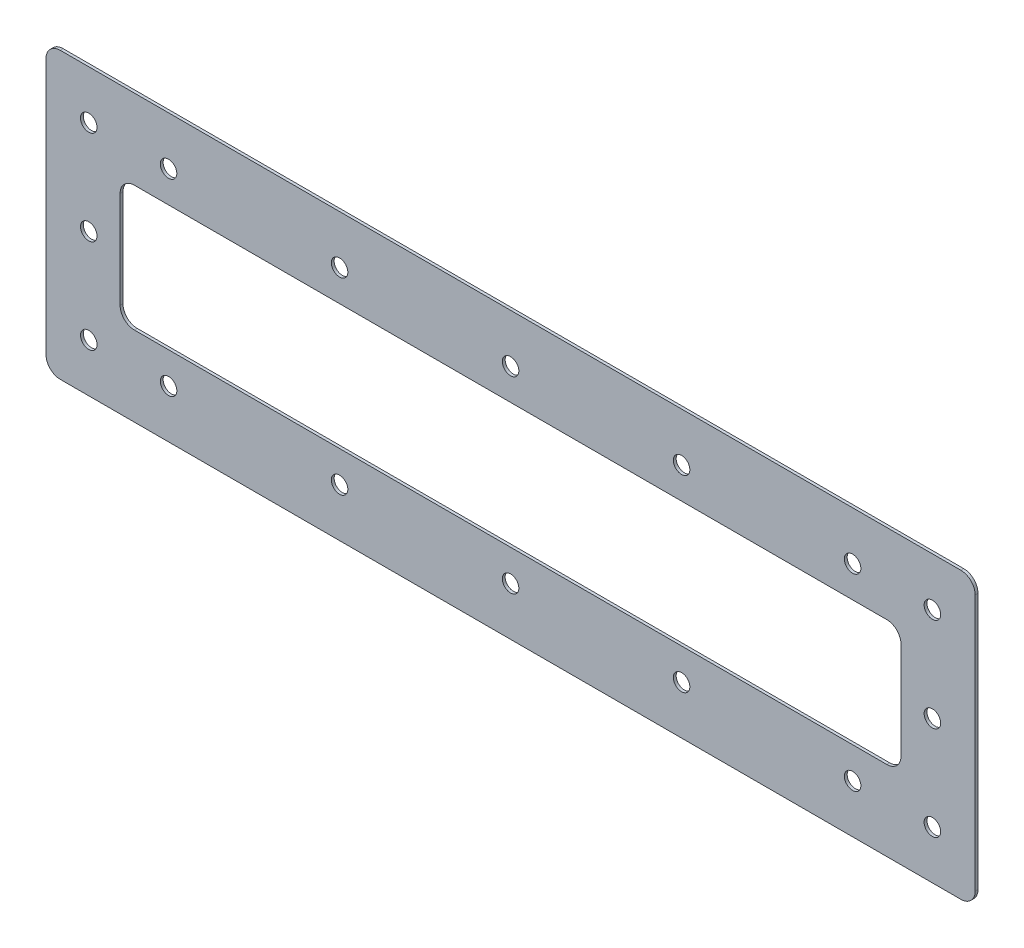
SolidWorks part; units mm, degrees
ref_plane "Front Plane" through (0, 0, 0) normal (0, 0, 1) x (1, 0, 0)
ref_plane "Top Plane" through (0, 0, 0) normal (0, 1, 0) x (1, 0, 0)
ref_plane "Right Plane" through (0, 0, 0) normal (1, 0, 0) x (0, 0, -1)
sketch "Sketch1" plane through (0, 0, 0) normal (0, 0, 1) x (1, 0, 0)
  line L1 (-163, -50) -> (163, -50)
  line L2 (-163, -50) -> (-163, 50)
  line L3 (-163, 50) -> (163, 50)
  line L4 (163, -50) -> (163, 50)
  line L5 (-163, -50) -> (163, 50) construction
  line L6 (-163, 50) -> (163, -50) construction
  line L7 (137, -22) -> (-137, -22)
  line L8 (137, -22) -> (137, 22)
  line L9 (137, 22) -> (-137, 22)
  line L10 (-137, -22) -> (-137, 22)
  line L11 (137, -22) -> (-137, 22) construction
  line L12 (137, 22) -> (-137, -22) construction
  point P0 (0, 0)
  point P6 (0, 0)
  dimension "D1" = 326
  dimension "D2" = 100
  dimension "D3" = 44
  dimension "D4" = 274
extrude "Boss-Extrude1" add sketch "Sketch1" along normal blind 1
fillet "Fillet1" radius 5 8 edges at (-137, -22, 0.5) (137, -22, 0.5) (137, 22, 0.5) (-137, 22, 0.5) (163, -50, 0.5) (-163, -50, 0.5) (163, 50, 0.5) (-163, 50, 0.5)
hole_wizard "M5 Clearance Hole1" positions "Sketch2" profile "Sketch3" hole size "M5" standard "ISO" end condition through all
sketch "Sketch2" plane through (0, 0, 0) normal (0, 0, -1) x (-1, 0, 0)
  point P0 (0, 33)
  point P3 (60, 33)
  point P6 (120, 33)
  point P9 (148, 33)
  point P12 (148, 0)
  point P15 (148, -33)
  point P18 (120, -33)
  point P21 (60, -33)
  point P24 (0, -33)
  point P27 (-60, 33)
  point P30 (-60, -33)
  point P33 (-120, -33)
  point P36 (-148, -33)
  point P39 (-148, 0)
  point P42 (-148, 33)
  point P45 (-120, 33)
sketch "Sketch3" plane through (0, 33, 0) normal (1, 0, 0) x (0, 1, 0)
  line L0 (0, 0) -> (0, 1)
  line L1 (0, 1) -> (2.9, 1)
  line L2 (2.9, 1) -> (2.9, 0)
  line L5 (2.9, 0) -> (0, 0)
  line L11 (0, -6.35) -> (0, 107.95) construction
  dimension "Thru Hole Dia." = 5.8
  dimension "Thru Hole Depth" = 1
